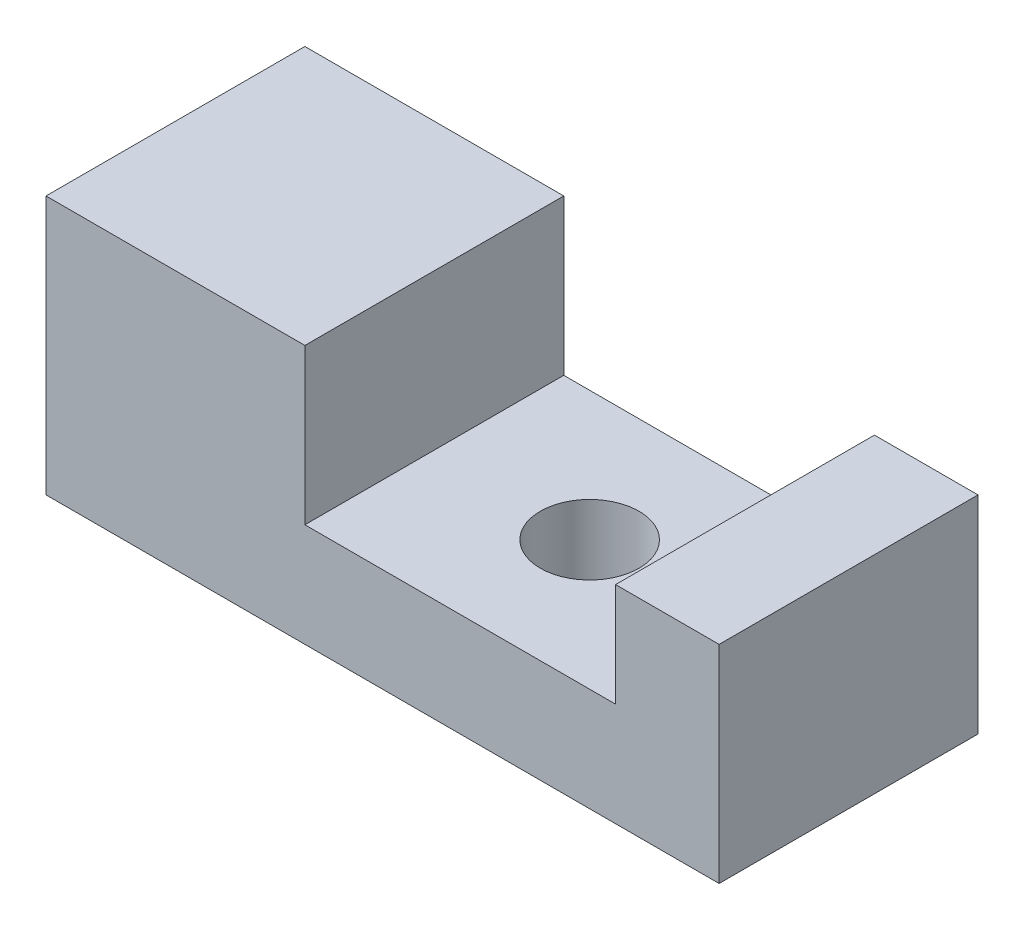
SolidWorks part; units mm, degrees
ref_plane "Front Plane" through (0, 0, 0) normal (0, 0, 1) x (1, 0, 0)
ref_plane "Top Plane" through (0, 0, 0) normal (0, 1, 0) x (1, 0, 0)
ref_plane "Right Plane" through (0, 0, 0) normal (1, 0, 0) x (0, 0, -1)
sketch "Sketch1" plane through (0, 0, 0) normal (0, 0, 1) x (1, 0, 0)
  line L0 (0, 0) -> (0, 50)
  line L1 (0, 50) -> (50, 50)
  line L2 (50, 50) -> (50, 20)
  line L3 (50, 20) -> (110, 20)
  line L4 (110, 20) -> (110, 40)
  line L5 (110, 40) -> (130, 40)
  line L6 (130, 40) -> (130, 0)
  line L7 (130, 0) -> (0, 0)
  dimension "D1" = 50
  dimension "D2" = 50
  dimension "D3" = 130
  dimension "D4" = 20
  dimension "D5" = 20
  dimension "D6" = 40
extrude "Boss-Extrude1" add sketch "Sketch1" along normal mid plane 50
sketch "Sketch5" plane through (0, 20, 0) normal (0, 1, 0) x (1, 0, 0)
  circle A0 centre (80, 0) radius 9.537
extrude "Cut-Extrude1" cut sketch "Sketch5" against normal through all
